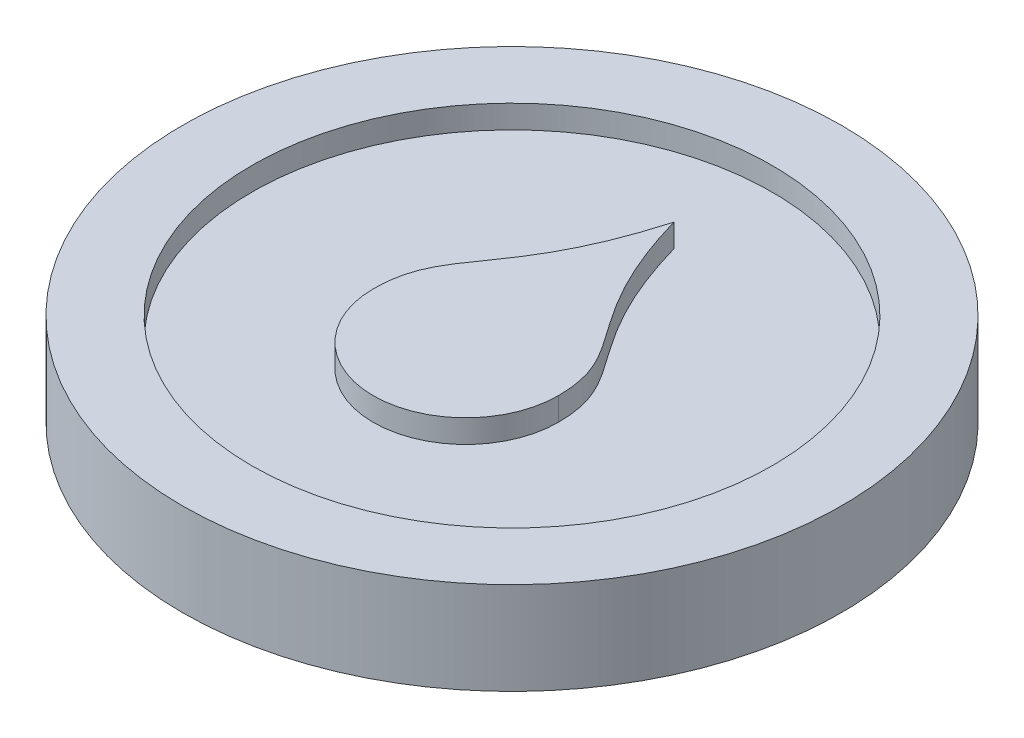
SolidWorks part; units mm, degrees
ref_plane "前视基准面" through (0, 0, 0) normal (0, 0, 1) x (1, 0, 0)
ref_plane "上视基准面" through (0, 0, 0) normal (0, 1, 0) x (1, 0, 0)
ref_plane "右视基准面" through (0, 0, 0) normal (1, 0, 0) x (0, 0, -1)
sketch "草图1" plane through (0, 0, 0) normal (0, 1, 0) x (1, 0, 0)
  circle A0 centre (0, 0) radius 14.25
  dimension "D1" = 28.5
extrude "凸台-拉伸1" add sketch "草图1" along normal blind 4
sketch "草图2" plane through (0, 4, 0) normal (0, 1, 0) x (1, 0, 0)
  circle A0 centre (0, 0) radius 14.25 construction
  circle A1 centre (0, 0) radius 14.25
  circle A2 centre (0, 0) radius 11.25
  dimension "D1" = 3
extrude "切除-拉伸1" cut sketch "草图2" against normal blind 1 contours A2
sketch "草图3" plane through (0, 3, 0) normal (0, 1, 0) x (1, 0, 0)
  line L0 (0, -0.3124) -> (0, 0) construction
  line L1 (-4, -2) -> (4, -2) construction
  line L2 (0, 0) -> (0, -2) construction
  line L3 (0, 0) -> (0, 7) construction
  line L4 (-4, 1.2146) -> (-4, -5.2353) construction
  arc A0 (-4, -2) -> (4, -2) centre (0, -2) ccw
  spline S0 degree 3 poles (-4, -2) (-4, 1.1714) (-1.6605, 1.197) (0, 7) knots 0 0 0 0 1 1 1 1
  spline S1 degree 3 poles (4, -2) (4, 1.1714) (1.6605, 1.197) (0, 7) knots 0 0 0 0 1 1 1 1
  dimension "D1" = 8
  dimension "D2" = 2
  dimension "D3" = 7
extrude "凸台-拉伸2" add sketch "草图3" along normal blind 1
